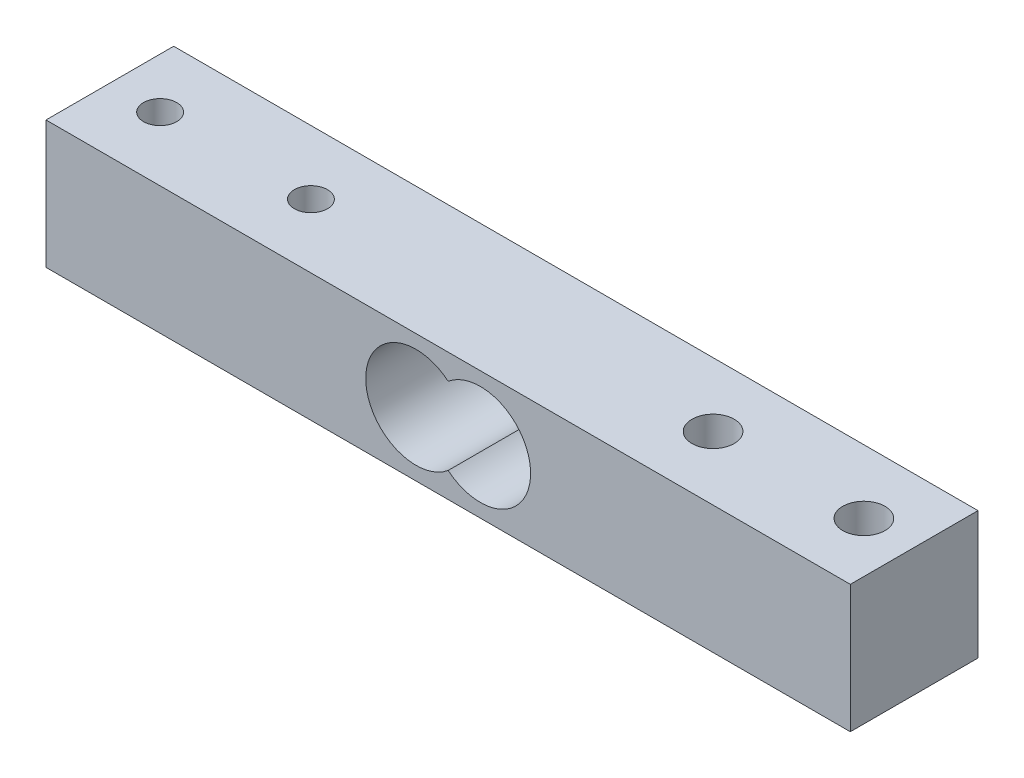
SolidWorks part; units mm, degrees
material "Aleación 1060"
ref_plane "Front" through (0, 0, 0) normal (0, 0, 1) x (1, 0, 0)
ref_plane "Top" through (0, 0, 0) normal (0, 1, 0) x (1, 0, 0)
ref_plane "Right" through (0, 0, 0) normal (1, 0, 0) x (0, 0, -1)
sketch "Croquis1" plane through (0, 0, 0) normal (0, 0, 1) x (1, 0, 0)
  line L0 (0, 0) -> (-3.2008, 0) construction
  line L1 (40, 6.35) -> (-40, 6.35)
  line L2 (40, 6.35) -> (40, -6.35)
  line L3 (40, -6.35) -> (-40, -6.35)
  line L4 (-40, 6.35) -> (-40, -6.35)
  line L5 (40, 6.35) -> (-40, -6.35) construction
  line L6 (40, -6.35) -> (-40, 6.35) construction
  line L7 (0, 0) -> (0, 3.8412) construction
  arc A0 (0, 3.8412) -> (0, -3.8412) centre (-3.2008, 0) ccw
  arc A1 (0, 3.8412) -> (0, -3.8412) centre (3.2008, 0) cw
  point P0 (0, 0)
  dimension "D1" = 80
  dimension "D4" = 5
  dimension "D2" = 12.7
  dimension "D3" = 3.2008
extrude "Saliente-Extruir1" add sketch "Croquis1" along normal blind 12.7
hole_wizard "Perforador para roscar para macho de roscar para M41" positions "Croquis2" profile "Croquis3" hole size "M4" standard "ISO" end condition through all
sketch "Croquis2" plane through (0, 6.35, 0) normal (0, 1, 0) x (1, 0, 0)
  line L0 (-40, -12.7) -> (-40, 0) construction
  point P0 (-35, -6.35)
  point P2 (-20, -6.35)
  dimension "D1" = 5
  dimension "D2" = 15
sketch "Croquis3" plane through (-35, 6.35, 6.35) normal (1, 0, 0) x (0, 0, 1)
  line L0 (0, 0) -> (0, 12.7)
  line L1 (0, 12.7) -> (1.65, 12.7)
  line L2 (1.65, 12.7) -> (1.65, 0)
  line L5 (1.65, 0) -> (0, 0)
  line L11 (0, -6.35) -> (0, 107.95) construction
  dimension "Diámetro de taladro hasta el siguiente" = 3.3
  dimension "Profundidad de taladro hasta el siguiente" = 12.7
hole_wizard "Perforador para roscar para macho de roscar para M52" positions "Croquis4" profile "Croquis5" size "M5" standard "ISO" slot yes end condition through all
sketch "Croquis4" plane through (0, 6.35, 0) normal (0, 1, 0) x (1, 0, 0)
  line L0 (40, -12.7) -> (40, 0) construction
  point P0 (35, -6.35)
  point P2 (20, -6.35)
  point P7 (40, -6.35)
  dimension "D1" = 15
  dimension "D2" = 5
sketch "Croquis5" plane through (35, 6.35, 6.35) normal (1, 0, 0) x (0, 0, 1)
  line L0 (0, 0) -> (0, 12.7)
  line L1 (0, 12.7) -> (2.1, 12.7)
  line L2 (2.1, 12.7) -> (2.1, 0)
  line L5 (2.1, 0) -> (0, 0)
  line L11 (0, -6.35) -> (0, 107.95) construction
  dimension "Diámetro de taladro hasta el siguiente" = 4.2
  dimension "Profundidad de taladro hasta el siguiente" = 12.7
sketch "Croquis6" plane through (0, 6.35, 0) normal (0, 1, 0) x (1, 0, 0)
  line L0 (40, -12.7) -> (-40, -12.7) construction
  line L1 (40, 0) -> (30, 0)
  line L2 (40, 0) -> (40, -12.7)
  line L3 (40, -12.7) -> (30, -12.7)
  line L4 (30, 0) -> (30, -12.7)
  dimension "D1" = 10
extrude "Saliente-Extruir2" [suppressed] add sketch "Croquis6" along normal blind 2
sketch "Croquis7" plane through (0, -6.35, 0) normal (0, -1, 0) x (1, 0, 0)
  line L1 (-40, -0.15) -> (-30, -0.15)
  line L2 (-40, -0.15) -> (-40, 12.85)
  line L3 (-40, 12.85) -> (-30, 12.85)
  line L4 (-30, -0.15) -> (-30, 12.85)
  line L5 (-35, 6.35) -> (-30, 6.35) construction
  point P7 (-30, 6.35)
  dimension "D1" = 10
  dimension "D2" = 13
extrude "Saliente-Extruir3" [suppressed] add sketch "Croquis7" along normal blind 2
